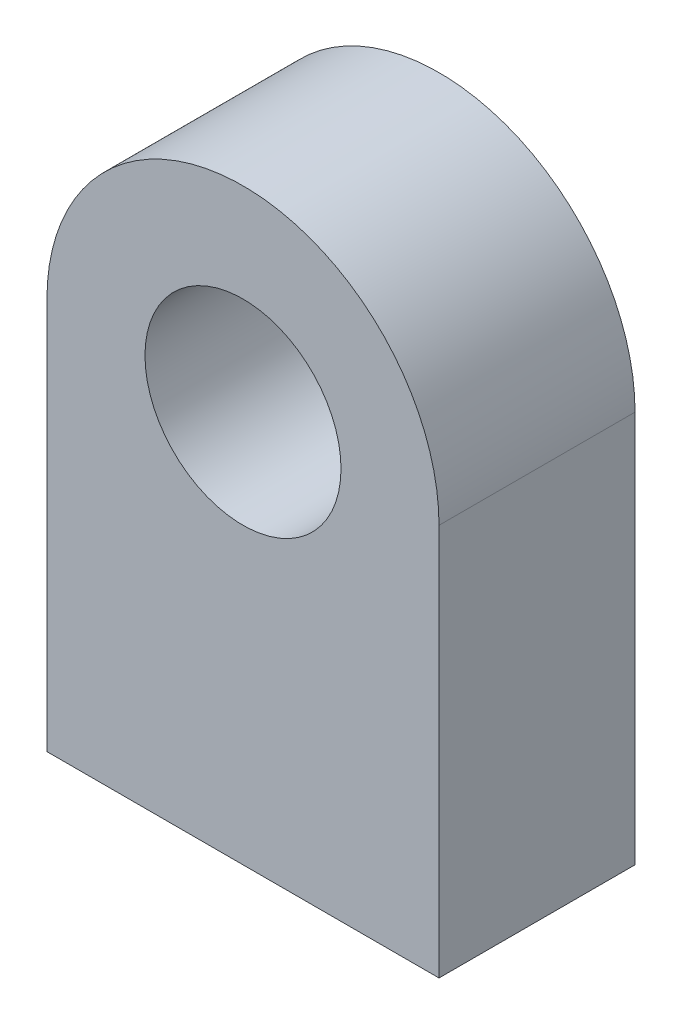
SolidWorks part; units mm, degrees
material "1060 Alloy"
ref_plane "Front Plane" through (0, 0, 0) normal (0, 0, 1) x (1, 0, 0)
ref_plane "Top Plane" through (0, 0, 0) normal (0, 1, 0) x (1, 0, 0)
ref_plane "Right Plane" through (0, 0, 0) normal (1, 0, 0) x (0, 0, -1)
sketch "Sketch1" plane through (0, 0, 0) normal (0, 0, 1) x (1, 0, 0)
  line L0 (0, 19.8538) -> (0, -21.8392) construction
  line L1 (-24.6755, 0) -> (26.59, 0) construction
  line L4 (-6.35, 0) -> (-6.35, -12.7)
  line L5 (-6.35, -12.7) -> (6.35, -12.7)
  line L6 (6.35, 0) -> (6.35, -12.7)
  line L7 (-2.8398, 5.6796) -> (6.35, -12.7) construction
  line L8 (-6.35, -12.7) -> (2.8398, 5.6796) construction
  circle A0 centre (0, 0) radius 3.175
  arc A1 (6.35, 0) -> (-6.35, 0) centre (0, 0) ccw
  point P12 (-6.35, 0)
  point P13 (0, 0)
  dimension "D1" = 6.35
  dimension "D2" = 12.7
  dimension "D3" = 12.7
extrude "Boss-Extrude1" add sketch "Sketch1" along normal blind 6.35
